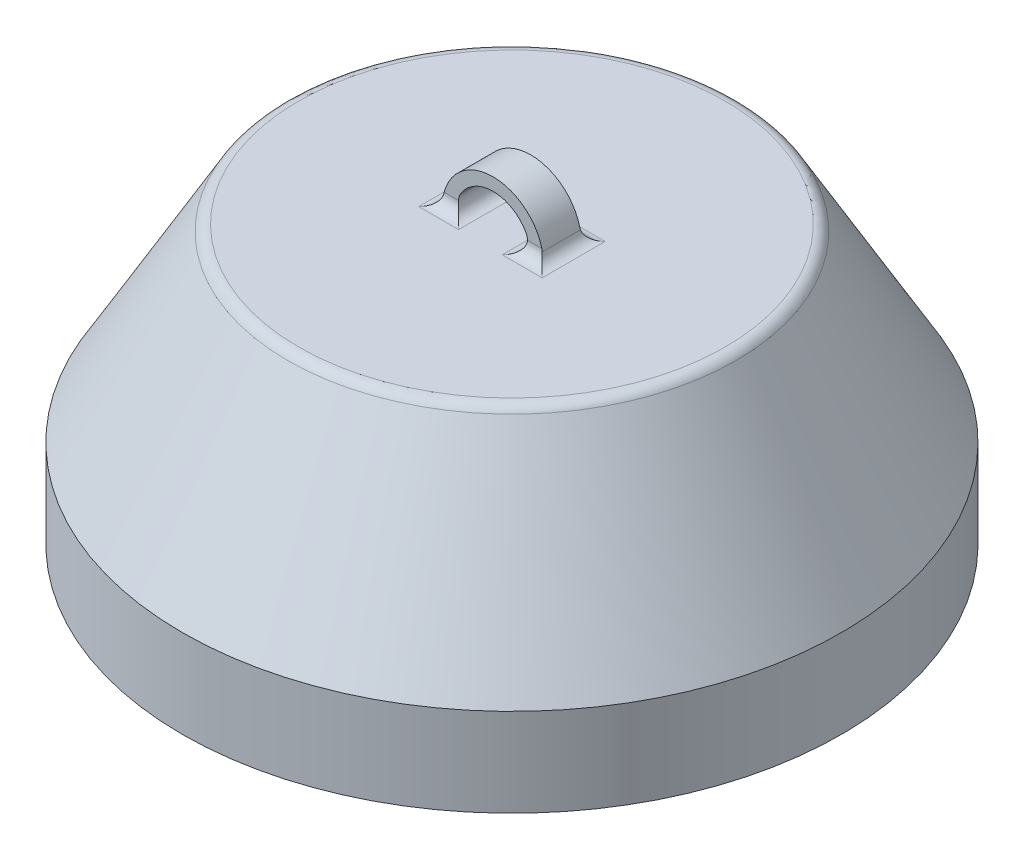
SolidWorks part; units mm, degrees
ref_plane "Front Plane" through (0, 0, 0) normal (0, 0, 1) x (1, 0, 0)
ref_plane "Top Plane" through (0, 0, 0) normal (0, 1, 0) x (1, 0, 0)
ref_plane "Right Plane" through (0, 0, 0) normal (1, 0, 0) x (0, 0, -1)
sketch "Sketch1" plane through (0, 0, 0) normal (0, 1, 0) x (1, 0, 0)
  circle A0 centre (0, 0) radius 24.65
  circle A1 centre (0, 0) radius 26.15
extrude "Boss-Extrude1" add sketch "Sketch1" along normal blind 7
sketch "Sketch3" plane through (0, 7, 0) normal (0, 1, 0) x (1, 0, 0)
  circle A0 centre (0, 0) radius 26.15
extrude "Boss-Extrude2" add sketch "Sketch3" along normal blind 15 draft 30
sketch "Sketch4" plane through (0, 7, 0) normal (0, -1, 0) x (1, 0, 0)
  circle A1 centre (0, 0) radius 24.65
extrude "Cut-Extrude1" cut sketch "Sketch4" against normal offset from surface 1.5 draft 30
sketch "Sketch5" plane through (0, 0, 0) normal (0, 0, 1) x (1, 0, 0)
  line L0 (17.4897, 22) -> (-17.4897, 22) construction
  line L1 (-4, 22) -> (-3, 22)
  line L2 (3, 22) -> (4, 22)
  arc A0 (4, 22) -> (-4, 22) centre (0, 22) ccw
  arc A1 (3, 22) -> (-3, 22) centre (0, 22) ccw
extrude "Boss-Extrude4" add sketch "Sketch5" along normal mid plane 3
fillet "Fillet2" radius 1 9 edges at (0, 22, 17.4897) (-4, 22, 0) (4, 22, 0) (-3.5, 22, -1.5) (3.5, 22, -1.5) (-3, 22, 0) (3, 22, 0) (-3.5, 22, 1.5) (3.5, 22, 1.5)
